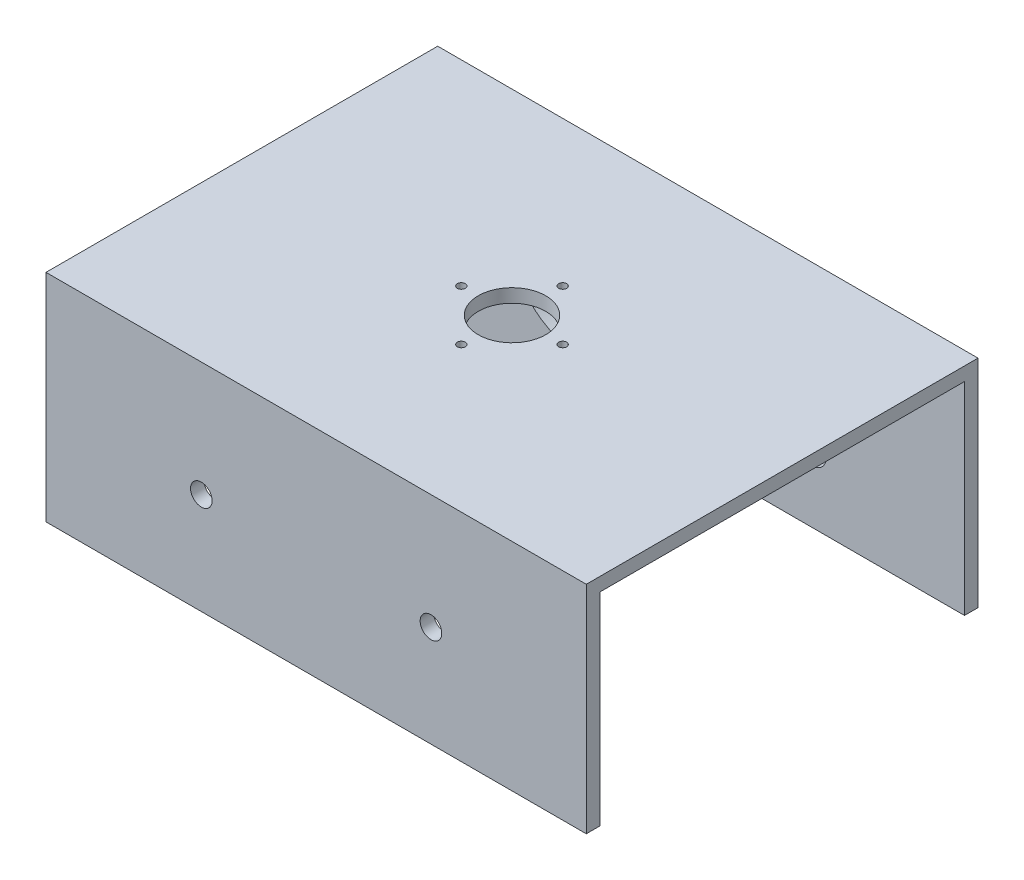
SolidWorks part; units mm, degrees
ref_plane "前视基准面" through (0, 0, 0) normal (0, 0, 1) x (1, 0, 0)
ref_plane "上视基准面" through (0, 0, 0) normal (0, 1, 0) x (1, 0, 0)
ref_plane "右视基准面" through (0, 0, 0) normal (1, 0, 0) x (0, 0, -1)
sketch "草图1" plane through (0, 0, 0) normal (0, 0, 1) x (1, 0, 0)
  line L1 (-40, -15) -> (40, -15)
  line L2 (-40, -15) -> (-40, 15)
  line L3 (-40, 15) -> (40, 15)
  line L4 (40, -15) -> (40, 15)
  line L5 (-40, -15) -> (40, 15) construction
  line L6 (-40, 15) -> (40, -15) construction
  point P0 (0, 0)
  dimension "D1" = 80
  dimension "D2" = 30
extrude "凸台-拉伸1" add sketch "草图1" along normal blind 2
sketch "草图2" plane through (0, 15, 0) normal (0, 1, 0) x (1, 0, 0)
  line L0 (-40, -2) -> (-40, 56)
  line L1 (-40, 56) -> (40, 56)
  line L2 (40, 56) -> (40, -2)
  line L4 (40, 0) -> (-40, 0)
  line L5 (-40, 0) -> (-40, -2)
  line L6 (-40, -2) -> (40, -2)
  line L7 (40, -2) -> (40, 0)
  line L10 (-40, -2) -> (40, -2)
  dimension "D2" = 58
  dimension "D1" = 0
extrude "凸台-拉伸2" add sketch "草图2" along normal blind 2
sketch "草图3" plane through (0, 15, 0) normal (0, -1, 0) x (1, 0, 0)
  line L0 (-40, -56) -> (40, -56)
  line L1 (40, -56) -> (40, -54)
  line L2 (40, 0) -> (40, -56) construction
  line L3 (40, -54) -> (-40, -54)
  line L4 (-40, -56) -> (-40, 0) construction
  line L5 (-40, -54) -> (-40, -56)
  dimension "D1" = 2
extrude "凸台-拉伸3" add sketch "草图3" along normal blind 30
sketch "草图5" plane through (0, 17, 0) normal (0, 1, 0) x (1, 0, 0)
  line L0 (-40, 27) -> (40, 27) construction
  line L1 (-40, 56) -> (-40, -2) construction
  line L2 (40, -2) -> (40, 56) construction
  line L3 (0, 56) -> (0, -2) construction
  line L4 (40, 56) -> (-40, 56) construction
  line L5 (-40, -2) -> (40, -2) construction
  circle A0 centre (0, 27) radius 5
  circle A1 centre (0, 27) radius 7.5 construction
  circle A2 centre (-7.5, 27) radius 0.6
  circle A3 centre (7.5, 27) radius 0.6
  circle A4 centre (0, 34.5) radius 0.6
  circle A5 centre (0, 19.5) radius 0.6
  dimension "D1" = 10
  dimension "D2" = 15
  dimension "D3" = 1.2
  dimension "D4" = 1.2
  dimension "D5" = 1.2
  dimension "D6" = 1.2
extrude "切除-拉伸1" cut sketch "草图5" against normal up to next
sketch "草图6" plane through (0, 0, -56) normal (0, 0, -1) x (-1, 0, 0)
  line L0 (-28.8431, 0) -> (27.4504, 0) construction
  circle A0 centre (-17, 0) radius 1.6
  circle A1 centre (17, 0) radius 1.6
  dimension "D1" = 3.2
  dimension "D2" = 3.2
  dimension "D3" = 17
  dimension "17" = 17
extrude "切除-拉伸3" cut sketch "草图6" against normal up to surface (58 mm away) up to face at (0, 1, 2)
sketch "草图7" plane through (0, 0, -56) normal (0, 0, -1) x (-1, 0, 0)
  circle A0 centre (17, 0) radius 10.1
  dimension "D1" = 20.2
extrude "切除-拉伸4" cut sketch "草图7" against normal up to next contours A0
sketch "草图8" plane through (0, 0, -54) normal (0, 0, 1) x (1, 0, 0)
  line L0 (40, -15) -> (40, 17) construction
  line L1 (-40, 17) -> (40, 17) construction
  circle A0 centre (17.42, 5) radius 2.1
  circle A1 centre (17.42, -5) radius 2.1
  dimension "D3" = 4.2
  dimension "D6" = 4.2
  dimension "D1" = 22.58
  dimension "D2" = 12
  dimension "D4" = 22.58
  dimension "D5" = 10
extrude "切除-拉伸5" cut sketch "草图8" against normal up to next
sketch "草图9" plane through (0, 0, -54) normal (0, 0, 1) x (1, 0, 0)
  line L0 (-40, 17) -> (40, 17) construction
  line L1 (-40, 17) -> (-40, -15) construction
  circle A0 centre (-32.07, 5) radius 2.1
  circle A1 centre (-32.07, -5) radius 2.1
  dimension "D5" = 4.2
  dimension "D6" = 4.2
  dimension "D1" = 12
  dimension "D2" = 7.93
  dimension "D3" = 7.93
  dimension "D4" = 10
extrude "切除-拉伸6" cut sketch "草图9" against normal up to next
